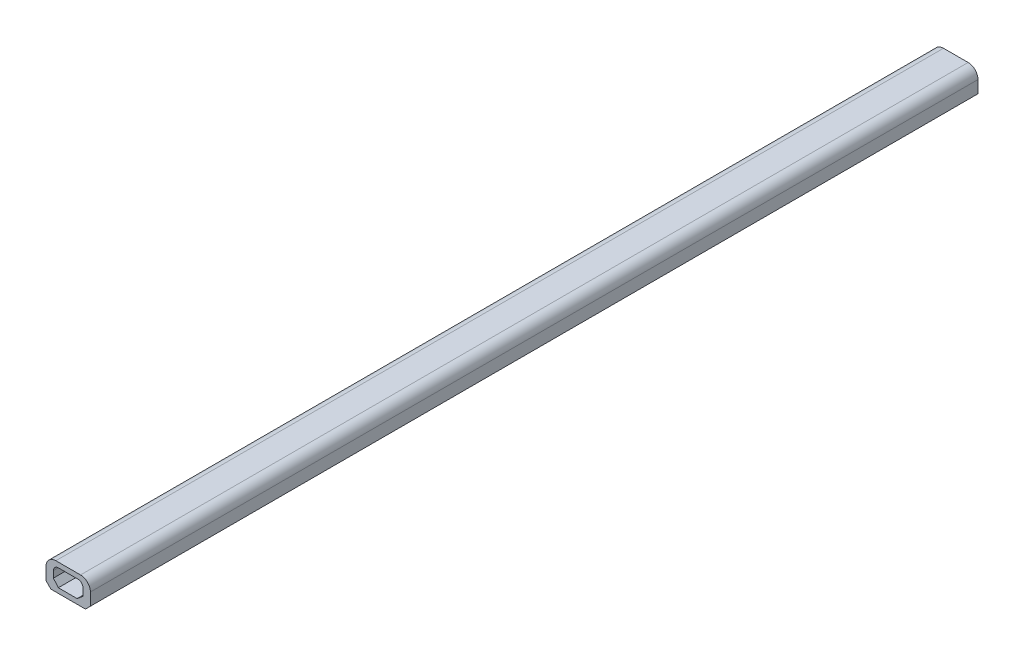
SolidWorks part; units mm, degrees
material "PAHT-CF"
ref_plane "Front Plane" through (0, 0, 0) normal (0, 0, 1) x (1, 0, 0)
ref_plane "Top Plane" through (0, 0, 0) normal (0, 1, 0) x (1, 0, 0)
ref_plane "Right Plane" through (0, 0, 0) normal (1, 0, 0) x (0, 0, -1)
sketch "Sketch1" plane through (0, 0, 0) normal (0, 0, 1) x (1, 0, 0)
  line L1 (0, 0) -> (9, 0)
  line L2 (0, 0) -> (0, -5.5)
  line L3 (0, -5.5) -> (9, -5.5)
  line L4 (9, 0) -> (9, -5.5)
  dimension "D1" = 5.5
  dimension "D2" = 9
extrude "Boss-Extrude1" add sketch "Sketch1" along normal blind 180
fillet "Fillet1" radius 2 2 edges at (0, 0, 90) (9, 0, 90)
chamfer "Chamfer1" distance 1 angle 45 2 edges at (0, -5.5, 90) (9, -5.5, 90)
sketch "Sketch2" plane through (0, 0, 0) normal (0, 0, -1) x (-1, 0, 0)
  line L0 (0, -2) -> (0, -4.5) construction
  line L1 (-1, -5.5) -> (0, -4.5) construction
  line L2 (-1, -5.5) -> (-8, -5.5) construction
  line L3 (-9, -4.5) -> (-8, -5.5) construction
  line L4 (-9, -4.5) -> (-9, -2) construction
  line L5 (-7, 0) -> (-2, 0) construction
  line L6 (0, -2) -> (0, -4.5)
  line L7 (-1, -5.5) -> (0, -4.5)
  line L8 (-1, -5.5) -> (-8, -5.5)
  line L9 (-9, -4.5) -> (-8, -5.5)
  line L10 (-9, -4.5) -> (-9, -2)
  line L11 (-7, 0) -> (-2, 0)
  line L13 (-7.5, -1) -> (-1.5, -1)
  line L14 (-7.5, -1) -> (-7.5, -4.5)
  line L15 (-7.5, -4.5) -> (-1.5, -4.5)
  line L16 (-1.5, -1) -> (-1.5, -4.5)
  arc A0 (0, -2) -> (-2, 0) centre (-2, -2) ccw construction
  arc A1 (-7, 0) -> (-9, -2) centre (-7, -2) ccw construction
  arc A2 (0, -2) -> (-2, 0) centre (-2, -2) ccw
  arc A3 (-7, 0) -> (-9, -2) centre (-7, -2) ccw
  dimension "D1" = 1.5
  dimension "D2" = 1.5
  dimension "D3" = 1
  dimension "D4" = 1
extrude "Cut-Extrude2" cut sketch "Sketch2" against normal through all contours L14 L13 L16 L15
fillet "Fillet2" radius 1 2 edges at (1.5, -1, 90) (7.5, -1, 90)
chamfer "Chamfer2" distance 1 angle 50 2 edges at (1.5, -4.5, 90) (7.5, -4.5, 90)
